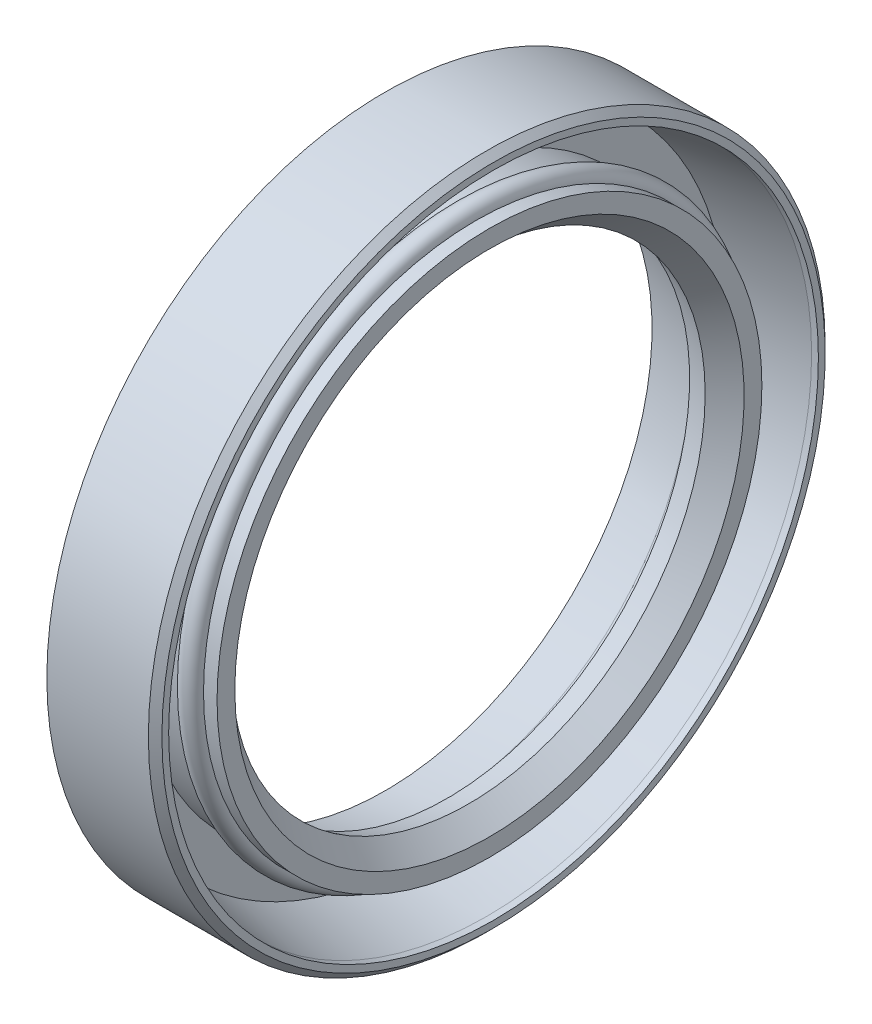
SolidWorks part; units mm, degrees
ref_plane "Front Plane" through (0, 0, 0) normal (0, 0, 1) x (1, 0, 0)
ref_plane "Top Plane" through (0, 0, 0) normal (0, 1, 0) x (1, 0, 0)
ref_plane "Right Plane" through (0, 0, 0) normal (1, 0, 0) x (0, 0, -1)
sketch "Sketch1" plane through (0, 0, 0) normal (0, 0, 1) x (1, 0, 0)
  line L0 (0, 25) -> (0, 19.7105)
  line L1 (0, 19.7105) -> (3.6, 19.0757)
  line L2 (4.5704, 17.9193) -> (6.1352, 17.5)
  line L4 (7.7, 20.1261) -> (6.7, 20.1261)
  line L5 (5.1, 20.1261) -> (2.1, 20.1261)
  line L6 (2.1, 20.1261) -> (2.1, 23.0478)
  line L7 (2.1, 23.0478) -> (7.5, 24)
  line L8 (7.5, 24) -> (8, 24)
  line L9 (8, 24) -> (8, 24.5)
  line L10 (7.5, 25) -> (0, 25)
  line L11 (8, 24.5) -> (7.5, 25)
  line L12 (6.1352, 17.5) -> (7.7, 18.813)
  line L13 (7.7, 18.813) -> (7.7, 20.1261)
  line L14 (4.5704, 17.9193) -> (4.5704, 17.5) construction
  line L15 (4.5704, 17.5) -> (6.1352, 17.5) construction
  line L16 (6.1352, 17.5) -> (7.7, 17.5) construction
  line L17 (7.7, 17.5) -> (7.7, 18.813) construction
  line L18 (2.1, 20.1261) -> (3.6, 19.0757) construction
  line L19 (5.1, 20.1261) -> (3.6, 19.0757) construction
  line L20 (0, 0) -> (21.4535, 0) construction
  arc A0 (3.6, 19.0757) -> (4.5704, 17.9193) centre (3.3961, 17.9193) cw
  arc A1 (6.7, 20.1261) -> (5.1, 20.1261) centre (5.9, 20.1261) ccw
  circle A2 centre (5.9, 20.1261) radius 0.5
  point P17 (8, 25)
  dimension "D3" = 0.8
  dimension "D16" = 1
  dimension "D1" = 8
  dimension "D2" = 0.5
  dimension "D4" = 1
  dimension "D6" = 3
  dimension "D7" = 0.2
  dimension "D8" = 7.5
  dimension "D9" = 25
  dimension "D10" = 100
  dimension "D11" = 1
  dimension "D12" = 80
  dimension "D13" = 15
  dimension "D14" = 40
  dimension "D15" = 35
revolve "Revolve1" add sketch "Sketch1" angle 360 about L20
sketch "Sketch2" plane through (0, 0, 0) normal (-1, 0, 0) x (0, 0, 1)
  line L0 (0, 0) -> (0, 25) construction
  circle A0 centre (0, 0) radius 25 construction
